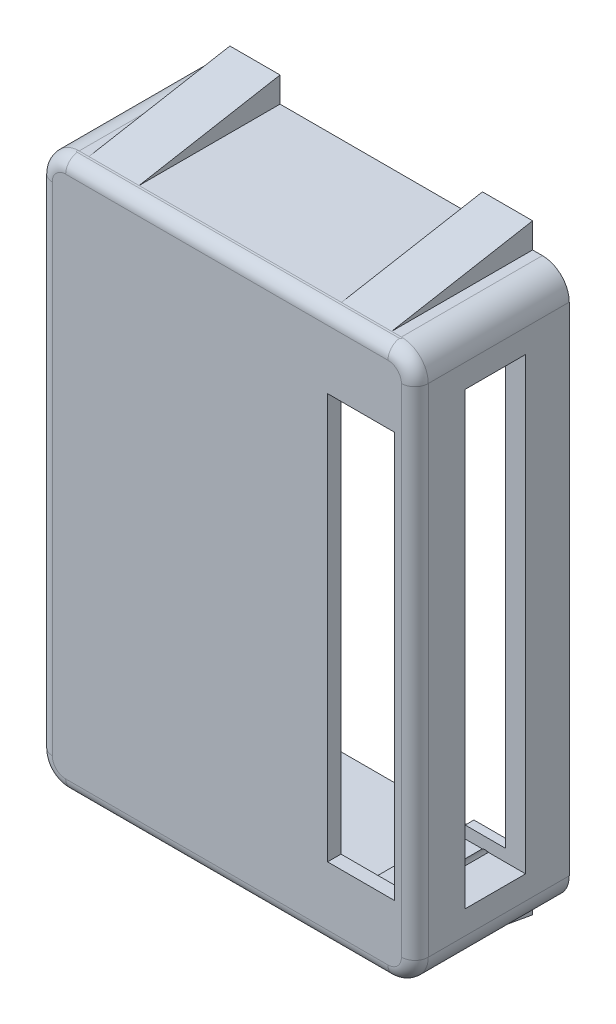
SolidWorks part; units mm, degrees
ref_plane "Alzado" through (0, 0, 0) normal (0, 0, 1) x (1, 0, 0)
ref_plane "Planta" through (0, 0, 0) normal (0, 1, 0) x (1, 0, 0)
ref_plane "Vista lateral" through (0, 0, 0) normal (1, 0, 0) x (0, 0, -1)
sketch "Croquis1" plane through (0, 0, 0) normal (0, 0, 1) x (1, 0, 0)
  line L1 (-25, 38) -> (25, 38)
  line L2 (-25, 38) -> (-25, -38)
  line L3 (-25, -38) -> (25, -38)
  line L4 (25, 38) -> (25, -38)
  line L5 (-25, 38) -> (25, -38) construction
  line L6 (-25, -38) -> (25, 38) construction
  point P0 (0, 0)
  dimension "D1" = 76
  dimension "D2" = 50
extrude "Extruir-Lámina1" add sketch "Croquis1" along normal blind 22 thin thin type one direction wall 3
fillet "Redondeo1" radius 4 1 edges at (-28, 41, 11)
fillet "Redondeo2" radius 4 1 edges at (28, 41, 11)
fillet "Redondeo3" radius 4 1 edges at (28, -41, 11)
fillet "Redondeo4" radius 4 1 edges at (-28, -41, 11)
sketch "Croquis2" plane through (0, 0, 22) normal (0, 0, 1) x (1, 0, 0)
  line L4 (-28, 37) -> (-28, -37)
  line L5 (-24, -41) -> (24, -41)
  line L6 (28, -37) -> (28, 37)
  line L7 (24, 41) -> (-24, 41)
  line L8 (-28, 37) -> (-28, -37)
  line L9 (-24, -41) -> (24, -41)
  line L10 (28, -37) -> (28, 37)
  line L11 (24, 41) -> (-24, 41)
  arc A4 (-28, -37) -> (-24, -41) centre (-24, -37) ccw
  arc A5 (24, -41) -> (28, -37) centre (24, -37) ccw
  arc A6 (28, 37) -> (24, 41) centre (24, 37) ccw
  arc A7 (-24, 41) -> (-28, 37) centre (-24, 37) ccw
  arc A8 (-28, -37) -> (-24, -41) centre (-24, -37) ccw
  arc A9 (24, -41) -> (28, -37) centre (24, -37) ccw
  arc A10 (28, 37) -> (24, 41) centre (24, 37) ccw
  arc A11 (-24, 41) -> (-28, 37) centre (-24, 37) ccw
  dimension "D1" = 0
extrude "Saliente-Extruir1" add sketch "Croquis2" along normal blind 1 and the other way blind 1
fillet "Redondeo5" radius 2 8 edges at (0, 41, 23) (26.8284, 39.8284, 23) (28, 0, 23) (26.8284, -39.8284, 23) (0, -41, 23) (-26.8284, -39.8284, 23) (-28, 0, 23) (-26.8284, 39.8284, 23)
sketch "Croquis3" plane through (0, 0, 21) normal (0, 0, -1) x (-1, 0, 0)
  line L0 (-25, 31.7) -> (-19, 31.7)
  line L1 (-25, 38) -> (-19, 38)
  line L2 (-25, 38) -> (-25, 31.7)
  line L3 (-25, -38) -> (-19, -38)
  line L4 (25, 38) -> (25, 31.7)
  line L5 (-25, -31.7) -> (-19, -31.7)
  line L6 (-19, -38) -> (-19, -31.7)
  line L7 (19, -38) -> (19, -31.7)
  line L8 (-19, 31.7) -> (-19, 38)
  line L9 (19, 31.7) -> (25, 31.7)
  line L10 (19, 31.7) -> (19, 38)
  line L11 (19, -31.7) -> (25, -31.7)
  line L12 (19, -38) -> (25, -38)
  line L13 (-25, -31.7) -> (-25, -38)
  line L14 (19, 38) -> (25, 38)
  line L15 (25, -31.7) -> (25, -38)
  dimension "D1" = 6.3
  dimension "D2" = 6.3
  dimension "D3" = 6
  dimension "D4" = 6
extrude "Saliente-Extruir2" add sketch "Croquis3" along normal blind 15.8
sketch "Croquis4" plane through (0, 0, 5.2) normal (0, 0, -1) x (-1, 0, 0)
  line L0 (25, 38) -> (25, -38) construction
  line L1 (-22, -34.5) -> (22, -34.5) construction
  line L2 (-22, -34.5) -> (-22, 34.5) construction
  line L3 (-22, 34.5) -> (22, 34.5) construction
  line L4 (22, -34.5) -> (22, 34.5) construction
  line L5 (-22, -34.5) -> (22, 34.5) construction
  line L6 (-22, 34.5) -> (22, -34.5) construction
  circle A0 centre (-22, 34.5) radius 0.75
  circle A1 centre (22, 34.5) radius 0.75
  circle A2 centre (22, -34.5) radius 0.75
  circle A3 centre (-22, -34.5) radius 0.75
  point P0 (0, 0)
  dimension "D2" = 1.5
  dimension "D3" = 1.5
  dimension "D4" = 1.5
  dimension "D5" = 1.5
  dimension "D1" = 3
  dimension "D6" = 69
extrude "Cortar-Extruir1" cut sketch "Croquis4" against normal blind 10
sketch "Croquis5" plane through (0, 0, 21) normal (0, 0, -1) x (-1, 0, 0)
  line L0 (-25, -31.7) -> (-25, 31.7) construction
  line L1 (-25, 30.2) -> (-15, 30.2)
  line L2 (-25, 30.2) -> (-25, -30.2)
  line L3 (-25, -30.2) -> (-15, -30.2)
  line L4 (-15, 30.2) -> (-15, -30.2)
  line L5 (-25, 31.7) -> (-19, 31.7) construction
  line L6 (-19, -31.7) -> (-25, -31.7) construction
  dimension "D1" = 10
  dimension "D2" = 1.5
  dimension "D3" = 1.5
extrude "Cortar-Extruir2" cut sketch "Croquis5" against normal blind 10
sketch "Croquis6" plane through (28, 0, 0) normal (1, 0, 0) x (0, 0, -1)
  line L1 (-15.5, 33.5) -> (-6.5, 33.5)
  line L2 (-15.5, 33.5) -> (-15.5, -33.5)
  line L4 (-6.5, 33.5) -> (-6.5, -33.5)
  line L5 (-23, -37) -> (-23, 37) construction
  line L6 (0, 37) -> (-21, 37) construction
  line L7 (-15.5, -33.5) -> (-6.5, -33.5)
  line L8 (-21, -37) -> (0, -37) construction
  dimension "D1" = 9
  dimension "D2" = 16.5
  dimension "D3" = 3.5
  dimension "D4" = 3.5
extrude "Cortar-Extruir4" cut sketch "Croquis6" against normal blind 10
sketch "Croquis7" plane through (0, 0, 0) normal (0, 0, -1) x (-1, 0, 0)
  line L0 (19, -38) -> (-19, -38) construction
  line L1 (23.8, -6) -> (27, -6)
  line L2 (23.8, -6) -> (23.8, -23)
  line L3 (23.8, -23) -> (27, -23)
  line L4 (27, -6) -> (27, -23)
  line L5 (28, 37) -> (28, -37) construction
  dimension "D1" = 15
  dimension "D2" = 17
  dimension "D3" = 3.2
  dimension "D4" = 1
extrude "Cortar-Extruir5" cut sketch "Croquis7" against normal blind 10
sketch "Croquis8" plane through (0, 0, 0) normal (0, 0, -1) x (-1, 0, 0)
  line L0 (24, 41) -> (-24, 41) construction
  line L1 (22.5441, 44.7626) -> (15.0747, 44.7626)
  line L2 (22.5441, 44.7626) -> (22.5441, 41)
  line L3 (22.5441, 41) -> (15.0747, 41)
  line L4 (15.0747, 44.7626) -> (15.0747, 41)
  line L5 (22.5441, 44.7626) -> (15.0747, 41) construction
  line L6 (22.5441, 41) -> (15.0747, 44.7626) construction
  line L7 (0, 0) -> (0, 43.8717) construction
  line L8 (0, 0) -> (36.4568, 0) construction
  line L9 (-22.5441, 41) -> (-15.0747, 44.7626) construction
  line L10 (-22.5441, 44.7626) -> (-15.0747, 41) construction
  line L11 (-15.0747, 44.7626) -> (-15.0747, 41)
  line L12 (-22.5441, 41) -> (-15.0747, 41)
  line L13 (-22.5441, 44.7626) -> (-22.5441, 41)
  line L14 (-22.5441, 44.7626) -> (-15.0747, 44.7626)
  line L15 (-22.5441, -44.7626) -> (-15.0747, -41) construction
  line L16 (-22.5441, -41) -> (-15.0747, -44.7626) construction
  line L17 (22.5441, -41) -> (15.0747, -44.7626) construction
  line L18 (22.5441, -44.7626) -> (15.0747, -41) construction
  line L19 (-22.5441, -44.7626) -> (-15.0747, -44.7626)
  line L20 (-22.5441, -44.7626) -> (-22.5441, -41)
  line L21 (-22.5441, -41) -> (-15.0747, -41)
  line L22 (-15.0747, -44.7626) -> (-15.0747, -41)
  line L23 (15.0747, -44.7626) -> (15.0747, -41)
  line L24 (22.5441, -41) -> (15.0747, -41)
  line L25 (22.5441, -44.7626) -> (22.5441, -41)
  line L26 (22.5441, -44.7626) -> (15.0747, -44.7626)
  point P0 (18.8094, 42.8813)
  point P15 (-18.8094, 42.8813)
  point P24 (-18.8094, -42.8813)
  point P25 (18.8094, -42.8813)
extrude "Saliente-Extruir3" add sketch "Croquis8" against normal blind 22
sketch "Croquis9" plane through (28, 0, 0) normal (1, 0, 0) x (0, 0, -1)
  line L0 (-21, 41) -> (0, 44.7626)
  line L1 (0, 44.7626) -> (0.1031, 48.489)
  line L2 (0.1031, 48.489) -> (-25.2043, 46.4362)
  line L3 (-25.2043, 46.4362) -> (-22.3149, 40.9027)
  line L4 (-22.3149, 40.9027) -> (-21, 41)
  line L5 (0, 0) -> (-35.2987, 0) construction
  line L6 (-22.3149, -40.9027) -> (-21, -41)
  line L7 (-25.2043, -46.4362) -> (-22.3149, -40.9027)
  line L8 (0.1031, -48.489) -> (-25.2043, -46.4362)
  line L9 (0, -44.7626) -> (0.1031, -48.489)
  line L10 (-21, -41) -> (0, -44.7626)
extrude "Cortar-Extruir6" cut sketch "Croquis9" against normal blind 85
sketch "Croquis10" plane through (0, 0, 0) normal (0, 0, -1) x (-1, 0, 0)
  line L1 (-19, -41.25) -> (19, -41.25) construction
  line L2 (-19, -41.25) -> (-19, 41.25) construction
  line L3 (-19, 41.25) -> (19, 41.25) construction
  line L4 (19, -41.25) -> (19, 41.25) construction
  line L5 (-19, -41.25) -> (19, 41.25) construction
  line L6 (-19, 41.25) -> (19, -41.25) construction
  circle A0 centre (-19, 41.25) radius 1.25
  circle A1 centre (19, 41.25) radius 1.25
  circle A2 centre (-19, -41.25) radius 1.25
  circle A3 centre (19, -41.25) radius 1.25
  point P0 (0, 0)
  dimension "D3" = 2.5
  dimension "D4" = 2.5
  dimension "D5" = 2.5
  dimension "D6" = 2.5
  dimension "D1" = 38
  dimension "D2" = 82.5
extrude "Cortar-Extruir7" cut sketch "Croquis10" against normal blind 10
sketch "Croquis11" plane through (0, 0, 5.2) normal (0, 0, -1) x (-1, 0, 0)
  circle A0 centre (-22, 34.5) radius 1.1
  circle A1 centre (22, 34.5) radius 1.1
  circle A2 centre (22, -34.5) radius 1.1
  circle A4 centre (-22, -34.5) radius 1.1
  dimension "D1" = 2.2
  dimension "D2" = 2.2
  dimension "D3" = 2.2
  dimension "D4" = 2.2
extrude "Cortar-Extruir8" cut sketch "Croquis11" against normal blind 10
